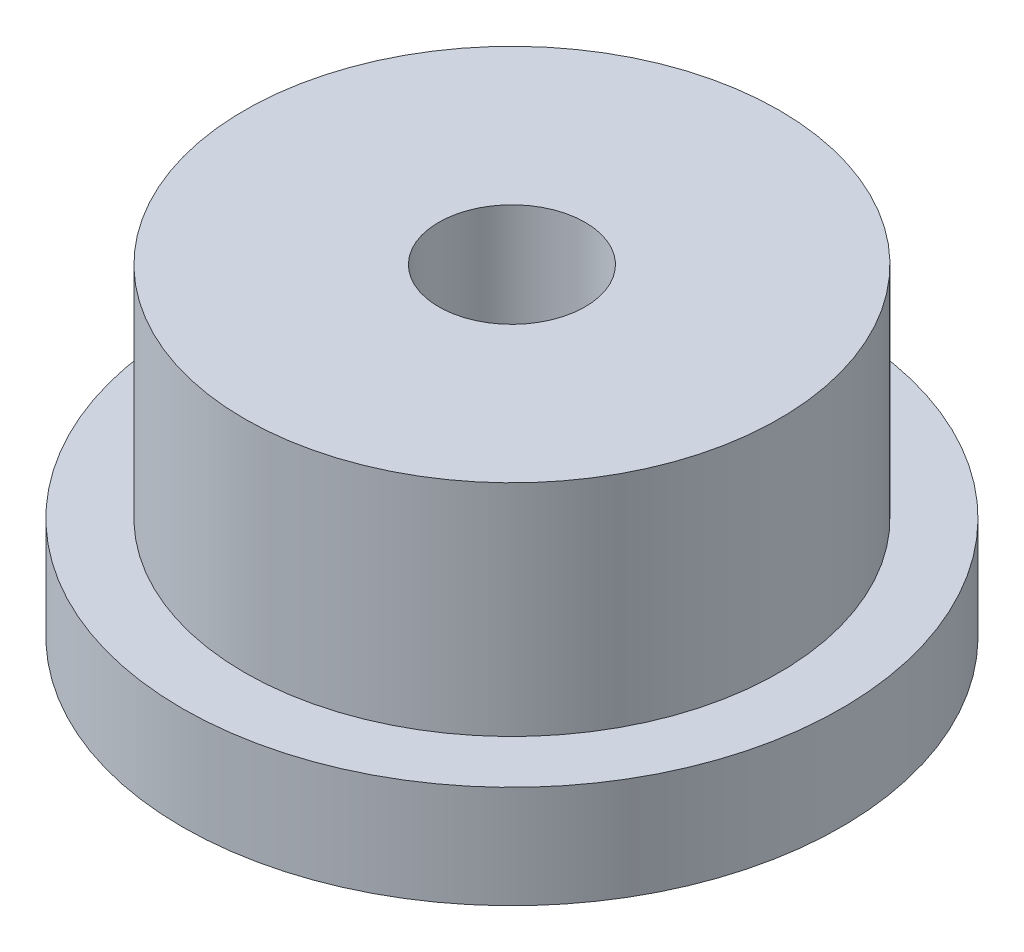
SolidWorks part; units mm, degrees
ref_plane "Front Plane" through (0, 0, 0) normal (0, 0, 1) x (1, 0, 0)
ref_plane "Top Plane" through (0, 0, 0) normal (0, 1, 0) x (1, 0, 0)
ref_plane "Right Plane" through (0, 0, 0) normal (1, 0, 0) x (0, 0, -1)
sketch "Sketch2" plane through (0, 0, 0) normal (0, 1, 0) x (1, 0, 0)
  circle A0 centre (0, 0) radius 22.5
  dimension "D1" = 45
extrude "Boss-Extrude1" add sketch "Sketch2" along normal blind 7
sketch "Sketch3" plane through (0, 7, 0) normal (0, 1, 0) x (1, 0, 0)
  circle A0 centre (0, 0) radius 18.25
  dimension "D1" = 36.5
extrude "Boss-Extrude2" add sketch "Sketch3" along normal blind 15
sketch "Sketch4" plane through (0, 0, 0) normal (0, -1, 0) x (-1, 0, 0)
  point P0 (0, 0)
hole_wizard "CBORE for M8 Hex Head Bolt1" positions "Sketch4" profile "Sketch5" counterbore size "M8" standard "ANSI Metric" end condition through all
sketch "Sketch5" plane through (0, 0, 0) normal (1, 0, 0) x (0, 0, -1)
  line L0 (0, 0) -> (0, 22)
  line L1 (0, 22) -> (5, 22)
  line L3 (5, 22) -> (5, 11.68)
  line L4 (9.005, 11.68) -> (5, 11.68)
  line L5 (9.005, 11.68) -> (9.005, 0.025)
  line L6 (9.005, 0.025) -> (9.03, 0)
  line L7 (9.03, 0) -> (0, 0)
  line L8 (-9.005, 0.025) -> (-9.03, 0) construction
  line L11 (0, -6.35) -> (0, 107.95) construction
  dimension "Thru Hole Dia." = 10
  dimension "Thru Hole Depth" = 22
  dimension "C'Bore Dia." = 18.01
  dimension "C'Bore Depth" = 11.68
  dimension "Near C'Sink Dia." = 18.06
  dimension "Near C'Sink Angle" = 90
